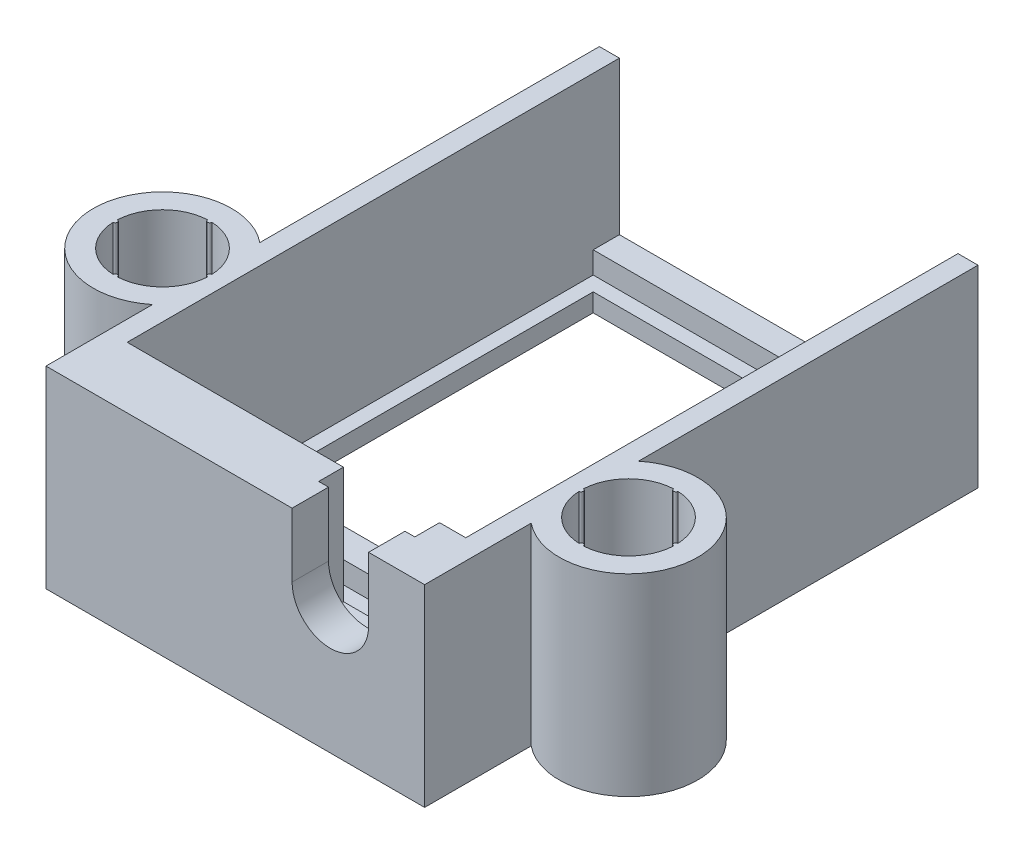
SolidWorks part; units mm, degrees
ref_plane "Front Plane" through (0, 0, 0) normal (0, 0, 1) x (1, 0, 0)
ref_plane "Top Plane" through (0, 0, 0) normal (0, 1, 0) x (1, 0, 0)
ref_plane "Right Plane" through (0, 0, 0) normal (1, 0, 0) x (0, 0, -1)
sketch "Sketch1" plane through (0, 0, 0) normal (0, 1, 0) x (1, 0, 0)
  line L0 (-16.3205, 0) -> (14.2146, 0) construction
  line L1 (0, 27.5343) -> (0, -22.2696) construction
  line L2 (-32.2463, -10) -> (35.4575, -10) construction
  line L3 (0, 27) -> (0, -10) construction
  line L4 (-13, 27) -> (13, 27)
  line L5 (-13, 27) -> (-13, -10)
  line L6 (-13, -10) -> (13, -10)
  line L7 (13, 27) -> (13, -10)
  circle A0 centre (-16, 0) radius 3.25
  circle A1 centre (-16, 0) radius 4.75
  circle A2 centre (16, 0) radius 3.25
  circle A3 centre (16, 0) radius 4.75
  dimension "D1" = 6.5
  dimension "D3" = 1.5
  dimension "D2" = 32
  dimension "D4" = 10
  dimension "D5" = 26
  dimension "D6" = 37
extrude "Boss-Extrude1" add sketch "Sketch1" along normal blind 13.25 contours L5 A1 A0 | L5 A1 A0 | L7 A3 L4 L5 A1 L6 | A3 L7 A2 | A3 L7 A2
sketch "Sketch2" plane through (0, 13.25, 0) normal (0, 1, 0) x (1, 0, 0)
  line L0 (0, 27) -> (0, -10) construction
  line L1 (-13, 27) -> (13, 27) construction
  line L2 (-13, -10) -> (13, -10) construction
  line L3 (0, -6.8) -> (0, 27) construction
  line L4 (-11.625, 27) -> (11.625, 27)
  line L5 (-11.625, 27) -> (-11.625, -6.8)
  line L6 (-11.625, -6.8) -> (11.625, -6.8)
  line L7 (11.625, 27) -> (11.625, -6.8)
  dimension "D1" = 23.25
  dimension "D2" = 3.2
extrude "Cut-Extrude1" cut sketch "Sketch2" against normal blind 12
sketch "Sketch3" plane through (0, 0, 10) normal (0, 0, 1) x (1, 0, 0)
  line L0 (9.825, 13.25) -> (9.825, 0) construction
  line L1 (-13, 13.25) -> (13, 13.25) construction
  line L2 (-13, 0) -> (13, 0) construction
  line L3 (11.625, 13.25) -> (11.625, 0) construction
  line L4 (3.225, 13.25) -> (3.225, 0) construction
  line L5 (3.225, 4.45) -> (9.825, 4.45) construction
  line L6 (6.525, 4.45) -> (6.525, 13.25) construction
  line L7 (3.9, 8.85) -> (3.9, 13.25)
  line L8 (9.15, 8.85) -> (9.15, 13.25)
  circle A0 centre (6.525, 8.85) radius 2.625
  line M3 (13, 13.25) -> (-13, 13.25)
  dimension "D4" = 5.25
  dimension "D1" = 1.8
  dimension "D2" = 6.6
  dimension "D3" = 8.8
extrude "Cut-Extrude2" cut sketch "Sketch3" against normal up to next contours A0 L8 L7 M3 | A0
sketch "Sketch4" plane through (0, 13.25, 0) normal (0, 1, 0) x (1, 0, 0)
  line L0 (6.525, -10) -> (6.525, -6.8) construction
  line L1 (3.9, -10) -> (9.15, -10) construction
  line L2 (9.15, -6.8) -> (3.9, -6.8) construction
  line L3 (-11.625, -6.8) -> (3.9, -6.8) construction
  line L4 (3.225, -6.8) -> (9.825, -6.8)
  line L5 (3.225, -6.8) -> (3.225, -8.5)
  line L6 (3.225, -8.5) -> (9.825, -8.5)
  line L7 (9.825, -6.8) -> (9.825, -8.5)
  line L8 (6.525, -8.5) -> (6.525, -6.8) construction
  dimension "D1" = 6.6
  dimension "D2" = 1.7
extrude "Cut-Extrude3" cut sketch "Sketch4" against normal blind 8
sketch "Sketch5" plane through (0, 1.25, 0) normal (0, 1, 0) x (1, 0, 0)
  line L0 (11.625, -6.8) -> (11.625, 27) construction
  line L1 (-11.625, -1.8) -> (11.625, -1.8)
  line L2 (-11.625, -1.8) -> (-11.625, 0.2)
  line L3 (-11.625, 0.2) -> (11.625, 0.2)
  line L4 (11.625, -1.8) -> (11.625, 0.2)
  line L5 (-11.625, 27) -> (-11.625, -6.8) construction
  line L6 (-11.625, 27) -> (11.625, 27)
  line L7 (-11.625, 27) -> (-11.625, 25.2)
  line L8 (-11.625, 25.2) -> (11.625, 25.2)
  line L9 (11.625, 27) -> (11.625, 25.2)
  line L10 (11.625, 27) -> (-11.625, 27) construction
  line L11 (-11.625, -6.8) -> (3.225, -6.8) construction
  line L12 (-11.625, -6.8) -> (11.625, -6.8) construction
  line L13 (-11.625, 27) -> (-11.625, -6.8) construction
  dimension "D1" = 7
  dimension "D2" = 32
  dimension "D3" = 2
extrude "Boss-Extrude2" add sketch "Sketch5" along normal blind 1.5
sketch "Sketch6" plane through (0, 1.25, 0) normal (0, 1, 0) x (1, 0, 0)
  line L4 (11.625, 0.2) -> (11.625, 25.2)
  line L5 (11.625, 25.2) -> (-11.625, 25.2)
  line L6 (-11.625, 25.2) -> (-11.625, 0.2)
  line L7 (-11.625, 0.2) -> (11.625, 0.2)
  line L8 (11.625, 0.2) -> (11.625, 25.2)
  line L9 (11.625, 25.2) -> (-11.625, 25.2)
  line L10 (-11.625, 25.2) -> (-11.625, 0.2)
  line L11 (-11.625, 0.2) -> (11.625, 0.2)
  line L16 (10.625, 1.2) -> (10.625, 24.2)
  line L17 (10.625, 24.2) -> (-10.625, 24.2)
  line L18 (-10.625, 24.2) -> (-10.625, 1.2)
  line L19 (-10.625, 1.2) -> (10.625, 1.2)
  line L20 (10.625, 1.2) -> (10.625, 24.2)
  line L21 (10.625, 24.2) -> (-10.625, 24.2)
  line L22 (-10.625, 24.2) -> (-10.625, 1.2)
  line L23 (-10.625, 1.2) -> (10.625, 1.2)
  dimension "D1" = 0
  dimension "D2" = 1
extrude "Cut-Extrude4" cut sketch "Sketch6" against normal up to next contours L22 L23 L20 L21
sketch "Sketch7" plane through (0, 13.25, 0) normal (0, 1, 0) x (1, 0, 0)
  line L0 (-16, 3.25) -> (-16, -3.25) construction
  line L1 (-19.25, 0) -> (-12.75, 0) construction
  line L2 (0, 27) -> (0, -10) construction
  line L3 (11.625, 27) -> (-11.625, 27) construction
  line L4 (-13, -10) -> (3.9, -10) construction
  circle A0 centre (-16, 0) radius 3.25 construction
  circle A1 centre (-16, 3.25) radius 0.15
  circle A2 centre (-19.25, 0) radius 0.15
  circle A3 centre (-12.75, 0) radius 0.15
  circle A4 centre (-16, -3.25) radius 0.15
  circle A5 centre (16, -3.25) radius 0.15
  circle A6 centre (12.75, 0) radius 0.15
  circle A7 centre (19.25, 0) radius 0.15
  circle A8 centre (16, 3.25) radius 0.15
  dimension "D1" = 0.3
extrude "Boss-Extrude3" add sketch "Sketch7" against normal up to surface (13.25 mm away) up to face at (0, 0, -12.7)
sketch "Sketch8" plane through (0, 0, 10) normal (0, 0, 1) x (1, 0, 0)
  line L7 (3.9, 8.85) -> (3.9, 13.25)
  line L8 (3.9, 13.25) -> (-13, 13.25)
  line L9 (-13, 13.25) -> (-13, 0)
  line L10 (-13, 0) -> (13, 0)
  line L11 (13, 0) -> (13, 13.25)
  line L12 (13, 13.25) -> (9.15, 13.25)
  line L13 (9.15, 13.25) -> (9.15, 8.85)
  line L14 (3.9, 8.85) -> (3.9, 13.25)
  line L15 (3.9, 13.25) -> (-13, 13.25)
  line L16 (-13, 13.25) -> (-13, 0)
  line L17 (-13, 0) -> (13, 0)
  line L18 (13, 0) -> (13, 13.25)
  line L19 (13, 13.25) -> (9.15, 13.25)
  line L20 (9.15, 13.25) -> (9.15, 8.85)
  arc A1 (3.9, 8.85) -> (9.15, 8.85) centre (6.525, 8.85) ccw
  arc A2 (3.9, 8.85) -> (9.15, 8.85) centre (6.525, 8.85) ccw
  dimension "D1" = 0
extrude "Boss-Extrude4" add sketch "Sketch8" along normal blind 1
